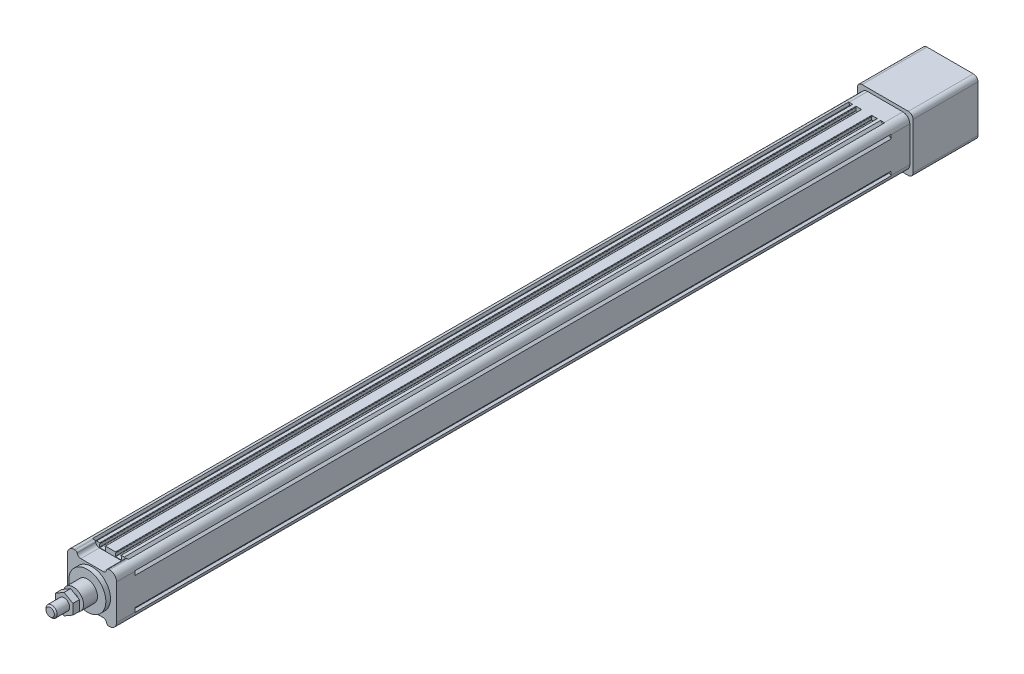
SolidWorks part; units mm, degrees
ref_plane "Front" through (0, 0, 0) normal (0, 0, 1) x (1, 0, 0)
ref_plane "Top" through (0, 0, 0) normal (0, 1, 0) x (1, 0, 0)
ref_plane "Right" through (0, 0, 0) normal (1, 0, 0) x (0, 0, -1)
sketch "草图1" plane through (0, 0, 0) normal (0, 0, 1) x (1, 0, 0)
  line L0 (19.7737, 3) -> (23.3, 3)
  line L1 (23.3, 3) -> (23.3, -3)
  line L2 (23.3, -3) -> (19.7737, -3)
  line L3 (-19.7737, -3) -> (-23.3, -3)
  line L4 (-23.3, -3) -> (-23.3, 3)
  line L5 (-23.3, 3) -> (-19.7737, 3)
  line L6 (-18.2, 24) -> (-19.4434, 26.4869)
  line L7 (-26.4869, 19.4434) -> (-24, 18.2)
  line L8 (-24, 18.2) -> (-24, 17.1)
  line L9 (-24, 17.1) -> (-26.5, 15)
  line L10 (-26.5, 15) -> (-26.5, -15)
  line L11 (-26.5, -15) -> (-24, -17.1)
  line L12 (-24, -17.1) -> (-24, -18.2)
  line L13 (-24, -18.2) -> (-26.4869, -19.4434)
  line L14 (-19.4434, -26.4869) -> (-18.2, -24)
  line L15 (-18.2, -24) -> (-17.1, -24)
  line L16 (-17.1, -24) -> (-15, -26.5)
  line L17 (-15, -26.5) -> (-11.65, -26.5)
  line L18 (-11.25, -26.1) -> (-11.25, -25.6)
  line L19 (-11.65, -25.2) -> (-11.75, -25.2)
  line L20 (-11.75, -25.2) -> (-11.75, -22.4)
  line L21 (-11.35, -22) -> (-5.65, -22)
  line L22 (-5.25, -22.4) -> (-5.25, -25.2)
  line L23 (-5.25, -25.2) -> (-5.35, -25.2)
  line L24 (-5.75, -25.6) -> (-5.75, -26.1)
  line L25 (-5.35, -26.5) -> (5.35, -26.5)
  line L26 (5.75, -26.1) -> (5.75, -25.6)
  line L27 (5.35, -25.2) -> (5.25, -25.2)
  line L28 (5.25, -25.2) -> (5.25, -22.4)
  line L29 (5.65, -22) -> (11.35, -22)
  line L30 (11.75, -22.4) -> (11.75, -25.2)
  line L31 (11.75, -25.2) -> (11.65, -25.2)
  line L32 (11.25, -25.6) -> (11.25, -26.1)
  line L33 (11.65, -26.5) -> (15, -26.5)
  line L34 (15, -26.5) -> (17.1, -24)
  line L35 (17.1, -24) -> (18.2, -24)
  line L36 (18.2, -24) -> (19.4434, -26.4869)
  line L37 (26.4869, -19.4434) -> (24, -18.2)
  line L38 (24, -18.2) -> (24, -17.1)
  line L39 (24, -17.1) -> (26.5, -15)
  line L40 (26.5, -15) -> (26.5, 15)
  line L41 (26.5, 15) -> (24, 17.1)
  line L42 (24, 17.1) -> (24, 18.2)
  line L43 (24, 18.2) -> (26.4869, 19.4434)
  line L44 (19.4434, 26.4869) -> (18.2, 24)
  line L45 (18.2, 24) -> (17.1, 24)
  line L46 (17.1, 24) -> (15, 26.5)
  line L47 (15, 26.5) -> (11.65, 26.5)
  line L48 (11.25, 26.1) -> (11.25, 25.6)
  line L49 (11.65, 25.2) -> (11.75, 25.2)
  line L50 (11.75, 25.2) -> (11.75, 22.4)
  line L51 (11.35, 22) -> (5.65, 22)
  line L52 (5.25, 22.4) -> (5.25, 25.2)
  line L53 (5.25, 25.2) -> (5.35, 25.2)
  line L54 (5.75, 25.6) -> (5.75, 26.1)
  line L55 (5.35, 26.5) -> (-5.35, 26.5)
  line L56 (-5.75, 26.1) -> (-5.75, 25.6)
  line L57 (-5.35, 25.2) -> (-5.25, 25.2)
  line L58 (-5.25, 25.2) -> (-5.25, 22.4)
  line L59 (-5.65, 22) -> (-11.35, 22)
  line L60 (-11.75, 22.4) -> (-11.75, 25.2)
  line L61 (-11.75, 25.2) -> (-11.65, 25.2)
  line L62 (-11.25, 25.6) -> (-11.25, 26.1)
  line L63 (-11.65, 26.5) -> (-15, 26.5)
  line L64 (-15, 26.5) -> (-17.1, 24)
  line L65 (-17.1, 24) -> (-18.2, 24)
  arc A0 (19.7737, 3) -> (-19.7737, 3) centre (0, 0) ccw
  arc A1 (-19.7737, -3) -> (19.7737, -3) centre (0, 0) ccw
  circle A2 centre (19, 19) radius 2.1
  circle A3 centre (19, -19) radius 2.1
  circle A4 centre (-19, -19) radius 2.1
  circle A5 centre (-19, 19) radius 2.1
  arc A6 (-19.4434, 26.4869) -> (-26.4869, 19.4434) centre (-19, 19) ccw
  arc A7 (-26.4869, -19.4434) -> (-19.4434, -26.4869) centre (-19, -19) ccw
  arc A8 (-11.65, -26.5) -> (-11.25, -26.1) centre (-11.65, -26.1) ccw
  arc A9 (-11.25, -25.6) -> (-11.65, -25.2) centre (-11.65, -25.6) ccw
  arc A10 (-11.35, -22) -> (-11.75, -22.4) centre (-11.35, -22.4) ccw
  arc A11 (-5.25, -22.4) -> (-5.65, -22) centre (-5.65, -22.4) ccw
  arc A12 (-5.35, -25.2) -> (-5.75, -25.6) centre (-5.35, -25.6) ccw
  arc A13 (-5.75, -26.1) -> (-5.35, -26.5) centre (-5.35, -26.1) ccw
  arc A14 (5.35, -26.5) -> (5.75, -26.1) centre (5.35, -26.1) ccw
  arc A15 (5.75, -25.6) -> (5.35, -25.2) centre (5.35, -25.6) ccw
  arc A16 (5.65, -22) -> (5.25, -22.4) centre (5.65, -22.4) ccw
  arc A17 (11.75, -22.4) -> (11.35, -22) centre (11.35, -22.4) ccw
  arc A18 (11.65, -25.2) -> (11.25, -25.6) centre (11.65, -25.6) ccw
  arc A19 (11.25, -26.1) -> (11.65, -26.5) centre (11.65, -26.1) ccw
  arc A20 (19.4434, -26.4869) -> (26.4869, -19.4434) centre (19, -19) ccw
  arc A21 (26.4869, 19.4434) -> (19.4434, 26.4869) centre (19, 19) ccw
  arc A22 (11.65, 26.5) -> (11.25, 26.1) centre (11.65, 26.1) ccw
  arc A23 (11.25, 25.6) -> (11.65, 25.2) centre (11.65, 25.6) ccw
  arc A24 (11.35, 22) -> (11.75, 22.4) centre (11.35, 22.4) ccw
  arc A25 (5.25, 22.4) -> (5.65, 22) centre (5.65, 22.4) ccw
  arc A26 (5.35, 25.2) -> (5.75, 25.6) centre (5.35, 25.6) ccw
  arc A27 (5.75, 26.1) -> (5.35, 26.5) centre (5.35, 26.1) ccw
  arc A28 (-5.35, 26.5) -> (-5.75, 26.1) centre (-5.35, 26.1) ccw
  arc A29 (-5.75, 25.6) -> (-5.35, 25.2) centre (-5.35, 25.6) ccw
  arc A30 (-5.65, 22) -> (-5.25, 22.4) centre (-5.65, 22.4) ccw
  arc A31 (-11.75, 22.4) -> (-11.35, 22) centre (-11.35, 22.4) ccw
  arc A32 (-11.65, 25.2) -> (-11.25, 25.6) centre (-11.65, 25.6) ccw
  arc A33 (-11.25, 26.1) -> (-11.65, 26.5) centre (-11.65, 26.1) ccw
extrude "凸台-拉伸1" add sketch "草图1" along normal blind 815
sketch "草图6" plane through (0, 0, 815) normal (0, 0, 1) x (1, 0, 0)
  line L0 (0, 0) -> (19, 0) construction
  line L2 (-26.5, -19) -> (-26.5, 19)
  line L3 (-19, 26.5) -> (-17.9161, 26.5)
  line L4 (26.5, -19) -> (26.5, 19)
  line L5 (-26.5, -26.5) -> (26.5, 26.5) construction
  line L6 (-26.5, 26.5) -> (26.5, -26.5) construction
  line L7 (-12, 21.5) -> (12, 21.5)
  line L9 (19, 26.5) -> (17.9161, 26.5)
  line L10 (19, -26.5) -> (17.9161, -26.5)
  line L11 (-12, -21.5) -> (12, -21.5)
  line L12 (-19, -26.5) -> (-17.9161, -26.5)
  arc A0 (12, 21.5) -> (15.9441, 24.8333) centre (12, 25.5) ccw
  arc A1 (-15.9441, 24.8333) -> (-12, 21.5) centre (-12, 25.5) ccw
  arc A2 (-15.9441, 24.8333) -> (-17.9161, 26.5) centre (-17.9161, 24.5) ccw
  arc A3 (15.9441, 24.8333) -> (17.9161, 26.5) centre (17.9161, 24.5) cw
  arc A4 (-26.5, -19) -> (-19, -26.5) centre (-19, -19) ccw
  arc A5 (19, -26.5) -> (26.5, -19) centre (19, -19) ccw
  arc A6 (26.5, 19) -> (19, 26.5) centre (19, 19) ccw
  arc A7 (-26.5, 19) -> (-19, 26.5) centre (-19, 19) cw
  arc A8 (15.9441, -24.8333) -> (17.9161, -26.5) centre (17.9161, -24.5) ccw
  arc A9 (12, -21.5) -> (15.9441, -24.8333) centre (12, -25.5) cw
  arc A10 (-15.9441, -24.8333) -> (-12, -21.5) centre (-12, -25.5) cw
  arc A11 (-15.9441, -24.8333) -> (-17.9161, -26.5) centre (-17.9161, -24.5) cw
  point P0 (0, 0)
  point P9 (0, 21.5)
  point P13 (20, 20.8461)
  point P16 (-12, 20.8461)
  dimension "D5" = 4
  dimension "D6" = 2
  dimension "D7" = 2
  dimension "D9" = 7.5
  dimension "D1" = 53
  dimension "D2" = 53
  dimension "D3" = 26.5
  dimension "D4" = 24
  dimension "D8" = 5
extrude "凸台-拉伸2" add sketch "草图6" along normal blind 20
sketch "草图7" plane through (0, 0, 835) normal (0, 0, 1) x (1, 0, 0)
  circle A0 centre (0, 0) radius 20
  dimension "D1" = 40
extrude "凸台-拉伸3" add sketch "草图7" along normal blind 5
sketch "草图9" plane through (0, 0, 840) normal (0, 0, 1) x (1, 0, 0)
  circle A0 centre (0, 0) radius 11
  dimension "D1" = 22
extrude "凸台-拉伸4" add sketch "草图9" along normal blind 15
sketch "草图10" plane through (0, 0, 855) normal (0, 0, 1) x (1, 0, 0)
  circle A0 centre (0, 0) radius 6
  dimension "D1" = 12
extrude "凸台-拉伸5" add sketch "草图10" along normal blind 25
sketch "草图11" plane through (0, 0, 0) normal (0, 0, -1) x (-1, 0, 0)
  line L1 (-19, -26.5) -> (19, -26.5)
  line L2 (-26.5, -19) -> (-26.5, 19)
  line L3 (-19, 26.5) -> (19, 26.5)
  line L4 (26.5, -19) -> (26.5, 19)
  line L5 (-26.5, -26.5) -> (26.5, 26.5) construction
  line L6 (-26.5, 26.5) -> (26.5, -26.5) construction
  arc A0 (-26.5, -19) -> (-19, -26.5) centre (-19, -19) ccw
  arc A1 (19, -26.5) -> (26.5, -19) centre (19, -19) ccw
  arc A2 (26.5, 19) -> (19, 26.5) centre (19, 19) ccw
  arc A3 (-26.5, 19) -> (-19, 26.5) centre (-19, 19) cw
  point P0 (0, 0)
  dimension "D3" = 7.5
  dimension "D1" = 53
  dimension "D2" = 53
extrude "凸台-拉伸6" add sketch "草图11" along normal blind 20
sketch "草图12" plane through (0, 0, -20) normal (0, 0, -1) x (-1, 0, 0)
  line L1 (-25, -30) -> (25, -30)
  line L2 (-30, -25) -> (-30, 25)
  line L3 (-25, 30) -> (25, 30)
  line L4 (30, -25) -> (30, 25)
  line L5 (-30, -30) -> (30, 30) construction
  line L6 (-30, 30) -> (30, -30) construction
  arc A0 (-30, -25) -> (-25, -30) centre (-25, -25) ccw
  arc A1 (25, -30) -> (30, -25) centre (25, -25) ccw
  arc A2 (30, 25) -> (25, 30) centre (25, 25) ccw
  arc A3 (-30, 25) -> (-25, 30) centre (-25, 25) cw
  point P0 (0, 0)
  dimension "D3" = 5
  dimension "D1" = 60
  dimension "D2" = 60
extrude "凸台-拉伸7" add sketch "草图12" along normal blind 70
sketch "草图14" plane through (0, 0, -90) normal (0, 0, -1) x (-1, 0, 0)
  circle A0 centre (0, 0) radius 19
  dimension "D1" = 38
extrude "切除-拉伸2" cut sketch "草图14" against normal blind 70
hole_wizard "M6 螺纹孔1" positions "草图15" profile "草图16" tap size "M6" standard "GB"
sketch "草图15" plane through (-26.5, 0, 0) normal (-1, 0, 0) x (0, 0, 1)
  line L0 (-20, -25) -> (-20, 25) construction
  line L1 (835, 19) -> (835, -19) construction
  point P0 (825, 11)
  point P2 (825, -11)
  point P4 (-10, 11)
  point P6 (-10, -11)
  dimension "D1" = 10
  dimension "D2" = 10
  dimension "D3" = 11
  dimension "D4" = 11
  dimension "D5" = 10
  dimension "D6" = 10
  dimension "D7" = 22
  dimension "D8" = 11
sketch "草图16" plane through (-26.5, 11, 825) normal (0, 1, 0) x (0, 0, 1)
  line L0 (0, 0) -> (0, 16.5022)
  line L1 (0, 16.5022) -> (2.5, 15)
  line L2 (2.5, 15) -> (2.5, 0)
  line L5 (2.5, 0) -> (0, 0)
  line L10 (0, 16.5022) -> (-2.5, 15) construction
  line L11 (0, -6.35) -> (0, 107.95) construction
  dimension "螺纹孔钻头直径" = 5
  dimension "螺纹孔钻头深度" = 15
  dimension "导头角度" = 118
cosmetic thread "孔螺蚊线4" parameters "D1"=12, "D2"=6
cosmetic thread "孔螺蚊线5" parameters "D1"=12, "D2"=6
cosmetic thread "孔螺蚊线6" parameters "D1"=12, "D2"=6
cosmetic thread "孔螺蚊线7" parameters "D1"=12, "D2"=6
chamfer "倒角1" distance 1.5 angle 45 1 edges at (6, 0, 880)
sketch "草图17" plane through (0, 0, 855) normal (0, 0, 1) x (1, 0, 0)
  line L1 (0, 10.9697) -> (-9.5, 5.4848)
  line L2 (-9.5, 5.4848) -> (-9.5, -5.4848)
  line L3 (-9.5, -5.4848) -> (0, -10.9697)
  line L4 (0, -10.9697) -> (9.5, -5.4848)
  line L5 (9.5, -5.4848) -> (9.5, 5.4848)
  line L6 (9.5, 5.4848) -> (0, 10.9697)
  circle A0 centre (0, 0) radius 9.5 construction
  dimension "D1" = 19
extrude "凸台-拉伸8" add sketch "草图17" along normal blind 7 from offset 3
